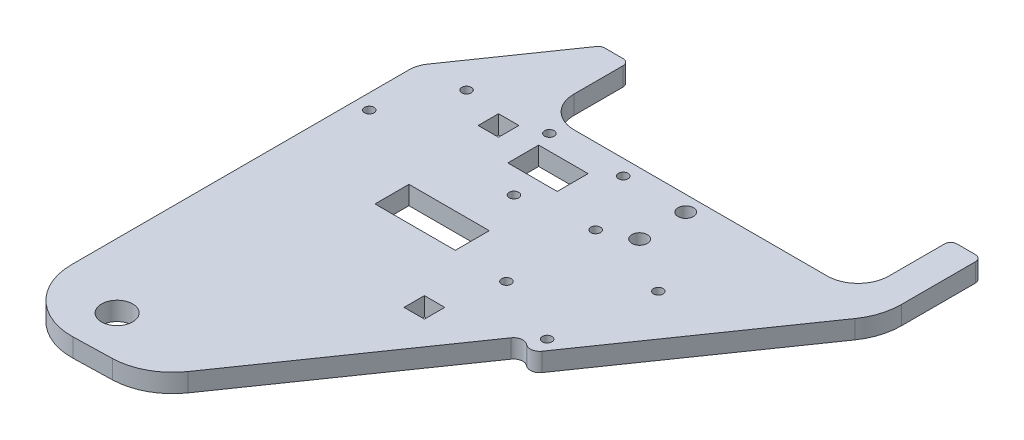
SolidWorks part; units mm, degrees
ref_plane "Płaszczyzna przednia" through (0, 0, 0) normal (0, 0, 1) x (1, 0, 0)
ref_plane "Płaszczyzna górna" through (0, 0, 0) normal (0, 1, 0) x (1, 0, 0)
ref_plane "Płaszczyzna prawa" through (0, 0, 0) normal (1, 0, 0) x (0, 0, -1)
sketch "Szkic2" plane through (0, 0, 0) normal (0, 1, 0) x (1, 0, 0)
  line L0 (-2.7059, 127.916) -> (-8.7059, 127.916)
  line L1 (-14.7059, 84.6961) -> (-30.2059, 84.6961)
  line L2 (-34.2059, 68.0362) -> (-34.2059, 10.6045)
  line L3 (103.2941, 130) -> (109.2941, 130)
  line L4 (56.7941, 30.9358) -> (56.7941, 25.7981)
  line L5 (56.7941, 59.3339) -> (56.7941, 30.9358)
  line L6 (14.1571, -19.1399) -> (-0.0957, -33.3284)
  line L7 (111.2941, 128) -> (111.2941, 110.0131)
  line L9 (9.2941, 100) -> (91.2941, 100)
  line L10 (85.9359, 90.0901) -> (91.3711, 90.0901)
  line L11 (-34.2059, 68.0362) -> (-34.2059, 69.9294)
  line L12 (-10.7059, 125.916) -> (-10.7059, 88.6961)
  line L13 (-34.2059, 69.9294) -> (-34.2059, 80.6961)
  line L14 (-34.2059, 10.6045) -> (-34.2059, -19.1544)
  line L15 (14.1571, -19.1399) -> (55.0272, 21.5459)
  line L26 (-0.7059, 110) -> (-0.7059, 125.916)
  line L28 (101.2941, 128) -> (101.2941, 110)
  arc A0 (56.7941, 25.7981) -> (55.0272, 21.5459) centre (50.7941, 25.7981) cw
  arc A1 (101.2941, 110) -> (91.2941, 100) centre (91.2941, 110) cw
  arc A2 (56.7941, 59.3339) -> (85.9359, 90.0901) centre (85.7027, 61.1269) cw
  arc A3 (-34.2059, -19.1544) -> (-0.0957, -33.3284) centre (-14.2059, -19.1544) ccw
  arc A4 (-34.2059, 80.6961) -> (-30.2059, 84.6961) centre (-30.2059, 80.6961) cw
  arc A5 (111.2941, 110.0131) -> (91.3711, 90.0901) centre (91.3711, 110.0131) cw
  arc A7 (-14.7059, 84.6961) -> (-10.7059, 88.6961) centre (-14.7059, 88.6961) ccw
  arc A8 (-8.7059, 127.916) -> (-10.7059, 125.916) centre (-8.7059, 125.916) ccw
  arc A9 (109.2941, 130) -> (111.2941, 128) centre (109.2941, 128) cw
  arc A10 (-0.7059, 110) -> (9.2941, 100) centre (9.2941, 110) ccw
  arc A11 (101.2941, 128) -> (103.2941, 130) centre (103.2941, 128) cw
  arc A12 (-2.7059, 127.916) -> (-0.7059, 125.916) centre (-2.7059, 125.916) cw
  point P0 (0.6391, -30.8544)
  point P1 (26.0174, 75.6612)
  point P7 (22.4343, 73.3976)
  point P9 (71.2941, 80)
  point P10 (-27.8527, -17.9733)
  point P18 (-27.4825, -20.4307)
  point P21 (71.2941, 110)
  dimension "D8" = 10
  dimension "D11" = 2
  dimension "D12" = 2
  dimension "D14" = 6
  dimension "D7" = 4
  dimension "D4" = 20
  dimension "D2" = 10
  dimension "D3" = 10
  dimension "D6" = 102
extrude "Dodanie-wyciągnięcie1" add sketch "Szkic2" along normal blind 6 separate body
sketch "Szkic3" plane through (0, 6, 0) normal (0, 1, 0) x (1, 0, 0)
  circle A4 centre (-13.2962, -25.3039) radius 5.05
  dimension "D2" = 10.1
  dimension "D1" = 0
extrude "Wytnij-wyciągnięcie1" cut sketch "Szkic3" against normal through all
sketch "Szkic4" plane through (0, 6, 0) normal (0, 1, 0) x (1, 0, 0)
  line L0 (4.8941, 92) -> (4.8941, 98) construction
  line L1 (7.9941, 92) -> (7.9941, 98) construction
  line L2 (31.8941, 92) -> (31.8941, 98) construction
  line L3 (28.7941, 92) -> (28.7941, 98) construction
  line L4 (37.8941, 73.9) -> (43.8941, 73.9) construction
  line L5 (37.8941, 45) -> (43.8941, 45) construction
  line L6 (37.8941, 48.1) -> (43.8941, 48.1) construction
  line L7 (37.8941, 77) -> (43.8941, 77) construction
  line L8 (4.8941, 92) -> (4.8941, 98)
  line L9 (7.9941, 92) -> (7.9941, 98)
  line L10 (31.8941, 92) -> (31.8941, 98)
  line L11 (28.7941, 92) -> (28.7941, 98)
  line L12 (7.827, 95) -> (4.8941, 95)
  line L13 (28.6269, 95) -> (31.8941, 95)
  line L14 (40.8941, 77) -> (40.8941, 73.9)
  line L15 (40.8941, 48.1) -> (40.8941, 45)
  line L36 (37.8941, 73.9) -> (43.8941, 73.9)
  line L37 (37.8941, 45) -> (43.8941, 45)
  line L38 (37.8941, 48.1) -> (43.8941, 48.1)
  line L39 (37.8941, 77) -> (43.8941, 77)
  circle A0 centre (40.8941, 46.55) radius 1.55
  circle A1 centre (40.8941, 75.45) radius 1.55
  circle A2 centre (6.3605, 95) radius 1.55
  circle A3 centre (30.2605, 95) radius 1.55
  dimension "D1" = 3.1
  dimension "D2" = 3.1
  dimension "D3" = 3.1
  dimension "D4" = 3.1
  dimension "D5" = 1.55
  dimension "D6" = 1.55
sketch "Szkic14" plane through (0, 0, 0) normal (0, -1, 0) x (1, 0, 0)
  line L0 (63.4524, -70.496) -> (70.9956, -63.931) construction
  line L1 (65.4876, -72.8344) -> (73.0308, -66.2694) construction
  line L2 (63.4524, -70.496) -> (70.9956, -63.931)
  line L3 (65.4876, -72.8344) -> (73.0308, -66.2694)
  line L4 (67.224, -67.2135) -> (69.2592, -69.5519)
  line L5 (-20.7559, -98.7461) -> (-20.7559, -88.7461) construction
  line L6 (-17.6559, -98.7461) -> (-17.6559, -88.7461) construction
  line L7 (-20.7559, -98.7461) -> (-20.7559, -88.7461)
  line L8 (-17.6559, -98.7461) -> (-17.6559, -88.7461)
  line L9 (-17.6559, -93.7461) -> (-20.7559, -93.7461)
  circle A0 centre (68.2416, -68.3827) radius 1.55
  circle A2 centre (-19.2059, -93.7461) radius 1.55
  dimension "D1" = 3.1
  dimension "D2" = 3.1
sketch "Szkic5" plane through (0, 6, 0) normal (0, 1, 0) x (1, 0, 0)
  line L3 (28.7941, 92) -> (7.9941, 92) construction
  line L4 (37.8941, 48.1) -> (37.8941, 73.9) construction
  line L5 (23.8941, 47) -> (23.8941, 58)
  line L6 (23.8941, 47) -> (-2.1059, 47)
  line L7 (23.8941, 58) -> (-2.1059, 58)
  line L8 (-2.1059, 47) -> (-2.1059, 58)
  line L9 (37.8941, 23) -> (37.8941, 45) construction
  line L10 (-1.1059, 29) -> (31.8941, 29) construction
  line L11 (23.8941, 90) -> (23.8941, 80)
  line L12 (23.8941, 90) -> (7.8941, 90)
  line L13 (23.8941, 80) -> (7.8941, 80)
  line L14 (7.8941, 90) -> (7.8941, 80)
  circle A0 centre (40.8941, 75.45) radius 1.55 construction
  circle A1 centre (30.2605, 95) radius 1.55 construction
  circle A2 centre (6.3605, 95) radius 1.55 construction
  circle A3 centre (40.8941, 46.55) radius 1.55 construction
  circle A4 centre (40.8941, 75.45) radius 1.55
  circle A5 centre (30.2605, 95) radius 1.55
  circle A6 centre (6.3605, 95) radius 1.55
  circle A7 centre (40.8941, 46.55) radius 1.55
  circle A10 centre (17.8941, 72) radius 1.55
  dimension "D1" = 11
  dimension "D2" = 26
  dimension "D4" = 18
  dimension "D5" = 2
  dimension "D6" = 10
  dimension "D9" = 3.1
  dimension "D3" = 14
  dimension "D7" = 20
  dimension "D8" = 20
  dimension "D10" = 16
extrude "Wytnij-wyciągnięcie2" cut sketch "Szkic5" against normal through all
sketch "Szkic12" plane through (0, 0, 0) normal (0, -1, 0) x (1, 0, 0)
  line L0 (28.4064, 21.7668) -> (22.6749, 30.0296)
  line L1 (-1.5055, 38.8356) -> (-13.6937, 39.1478)
  line L2 (55.0272, -21.5459) -> (-13.6937, 39.1478)
  line L4 (111.2941, -110.0131) -> (111.2941, -103.9866)
  line L5 (89.1661, -65.8281) -> (107.7277, -92.5876)
  line L6 (111.2941, -110.0131) -> (91.3711, -90.0901)
  line L7 (-1.5055, 38.8356) -> (6.7535, 38.624)
  line L10 (56.7941, -25.7981) -> (56.7941, -59.3339)
  line L11 (85.9359, -90.0901) -> (91.3711, -90.0901)
  line L12 (62.7753, -27.7816) -> (89.1661, -65.8281)
  line L13 (62.7753, -27.7816) -> (28.4064, 21.7668)
  arc A0 (-0.0957, 33.3284) -> (-34.2059, 19.1544) centre (-14.2059, 19.1544) ccw construction
  arc A1 (6.7535, 38.624) -> (22.6749, 30.0296) centre (6.2413, 18.6306) cw
  arc A2 (111.2941, -103.9866) -> (107.7277, -92.5876) centre (91.2941, -103.9866) ccw
  arc A6 (56.7941, -25.7981) -> (55.0272, -21.5459) centre (50.7941, -25.7981) ccw
  arc A7 (56.7941, -59.3339) -> (85.9359, -90.0901) centre (85.7027, -61.1269) ccw
  dimension "D1" = 20
extrude "Dodanie-wyciągnięcie2" add sketch "Szkic12" against normal blind 6
sketch "Szkic6" plane through (0, 0, 0) normal (0, -1, 0) x (1, 0, 0)
  circle A1 centre (68.2416, -68.3827) radius 1.55 construction
  circle A2 centre (68.2416, -68.3827) radius 1.55
extrude "Wytnij-wyciągnięcie3" cut sketch "Szkic6" against normal through all
sketch "Szkic13" plane through (0, 0, 0) normal (0, -1, 0) x (1, 0, 0)
  line L12 (-34.2059, -80.6961) -> (-34.2059, -90.1835)
  line L13 (11.8543, -159.0896) -> (-73.1985, -36.4725)
  line L14 (-10.3657, -127.0559) -> (-32.7793, -94.7431)
  line L15 (-8.7223, -127.916) -> (-6.2646, -127.916)
  line L16 (-2.7059, -127.916) -> (-8.7059, -127.916) construction
  line L17 (-8.7059, -80.6961) -> (-34.2059, -80.6961)
  line L18 (-6.2646, -127.916) -> (-6.2646, -80.6961)
  line L19 (-6.2646, -80.6961) -> (-8.7059, -80.6961)
  arc A11 (-34.2059, -90.1835) -> (-32.7793, -94.7431) centre (-26.2059, -90.1835) ccw
  arc A12 (-8.7223, -127.916) -> (-10.3657, -127.0559) centre (-8.7223, -125.916) cw
  dimension "D2" = 8
  dimension "D3" = 2
  dimension "D1" = 116.68
extrude "Dodanie-wyciągnięcie3" add sketch "Szkic13" against normal blind 6
sketch "Szkic9" plane through (0, 0, 0) normal (0, -1, 0) x (1, 0, 0)
  line L0 (107.7277, -92.5876) -> (22.6749, 30.0296) construction
  circle A0 centre (63.6687, -36.9649) radius 1.55
  circle A1 centre (-13.2962, 25.3039) radius 5.05 construction
  dimension "D1" = 3.1
  dimension "D2" = 4.5
  dimension "D3" = 99
extrude "Wytnij-wyciągnięcie5" cut sketch "Szkic9" against normal blind 6
sketch "Szkic11" plane through (0, 0, 0) normal (0, -1, 0) x (1, 0, 0)
  circle A0 centre (-29.3372, -72.3879) radius 1.55 construction
  circle A1 centre (-29.3372, -72.3879) radius 1.55
extrude "Wytnij-wyciągnięcie6" cut sketch "Szkic11" against normal blind 6
sketch "Szkic15" plane through (0, 0, 0) normal (0, -1, 0) x (1, 0, 0)
  circle A0 centre (50.5658, -80.0013) radius 2.5 construction
  circle A1 centre (50.4845, -95.0011) radius 2.5 construction
  circle A2 centre (50.5658, -80.0013) radius 2.5
  circle A3 centre (50.4845, -95.0011) radius 2.5
extrude "Wytnij-wyciągnięcie7" cut sketch "Szkic15" against normal blind 6
sketch "Szkic8" plane through (0, 0, 0) normal (0, -1, 0) x (1, 0, 0)
  circle A2 centre (-19.2059, -93.7461) radius 1.55 construction
  circle A3 centre (-19.2059, -93.7461) radius 1.55
extrude "Wytnij-wyciągnięcie4" cut sketch "Szkic8" against normal through all
sketch "Szkic17" plane through (0, 0, 0) normal (0, -1, 0) x (1, 0, 0)
  line L0 (31.8941, -29) -> (31.8941, -23) construction
  line L1 (31.8941, -29) -> (31.8941, -23)
  line L2 (31.8941, -23) -> (37.8941, -23) construction
  line L3 (37.8941, -23) -> (37.8941, -29) construction
  line L4 (37.8941, -29) -> (31.8941, -29) construction
  line L5 (31.8941, -23) -> (37.8941, -23)
  line L6 (37.8941, -23) -> (37.8941, -29)
  line L7 (37.8941, -29) -> (31.8941, -29)
  line L8 (-1.1059, -86) -> (-1.1059, -92) construction
  line L9 (-1.1059, -92) -> (-7.1059, -92) construction
  line L10 (38.1941, -29.3) -> (31.5941, -29.3)
  line L11 (31.5941, -29.3) -> (31.5941, -22.7)
  line L12 (31.5941, -22.7) -> (38.1941, -22.7)
  line L13 (38.1941, -22.7) -> (38.1941, -29.3)
  line L14 (-0.8059, -85.7) -> (-0.8059, -92.3)
  line L15 (-0.8059, -92.3) -> (-7.4059, -92.3)
  line L16 (-7.4059, -92.3) -> (-7.4059, -85.7)
  line L17 (-7.4059, -85.7) -> (-0.8059, -85.7)
  line L30 (-7.1059, -86) -> (-1.1059, -86) construction
  line L31 (-7.1059, -92) -> (-7.1059, -86) construction
  line L32 (-1.1059, -86) -> (-1.1059, -92)
  line L33 (-1.1059, -92) -> (-7.1059, -92)
  line L34 (-7.1059, -86) -> (-1.1059, -86)
  line L35 (-7.1059, -92) -> (-7.1059, -86)
  dimension "D1" = 0.3
  dimension "D2" = 0.3
sketch "Szkic20" plane through (0, 0, 0) normal (0, -1, 0) x (1, 0, 0)
  line L0 (38.1941, -22.7) -> (38.1941, -29.3) construction
  line L1 (38.1941, -29.3) -> (31.5941, -29.3) construction
  line L2 (31.5941, -29.3) -> (31.5941, -22.7) construction
  line L3 (31.5941, -22.7) -> (38.1941, -22.7) construction
  line L4 (-0.8059, -85.7) -> (-0.8059, -92.3) construction
  line L5 (-0.8059, -92.3) -> (-7.4059, -92.3) construction
  line L6 (-7.4059, -92.3) -> (-7.4059, -85.7) construction
  line L7 (-7.4059, -85.7) -> (-0.8059, -85.7) construction
  line L8 (38.1941, -22.7) -> (38.1941, -29.3)
  line L9 (38.1941, -29.3) -> (31.5941, -29.3)
  line L10 (31.5941, -29.3) -> (31.5941, -22.7)
  line L11 (31.5941, -22.7) -> (38.1941, -22.7)
  line L12 (-0.8059, -85.7) -> (-0.8059, -92.3)
  line L13 (-0.8059, -92.3) -> (-7.4059, -92.3)
  line L14 (-7.4059, -92.3) -> (-7.4059, -85.7)
  line L15 (-7.4059, -85.7) -> (-0.8059, -85.7)
extrude "Wytnij-wyciągnięcie9" cut sketch "Szkic20" against normal blind 6
sketch "Szkic21" plane through (0, 0, 0) normal (0, -1, 0) x (1, 0, 0)
  line L0 (62.0515, -32.0016) -> (61.6406, -32.2866)
  line L1 (66.2263, -32.7568) -> (22.6749, 30.0296)
  line L2 (57.4657, -31.5314) -> (14.6211, 30.2359)
  line L3 (6.7535, 38.624) -> (-1.3002, 38.8303)
  line L4 (107.7277, -92.5876) -> (22.6749, 30.0296) construction
  line L5 (6.7535, 38.624) -> (-13.6937, 39.1478) construction
  circle A0 centre (63.6687, -36.9649) radius 1.55 construction
  arc A1 (61.6406, -32.2866) -> (57.4657, -31.5314) centre (59.9308, -29.8215) cw
  arc A2 (66.2263, -32.7568) -> (62.0515, -32.0016) centre (63.7613, -34.4666) ccw
  arc A3 (-1.3002, 38.8303) -> (14.6211, 30.2359) centre (-1.8124, 18.8369) cw
  arc A4 (22.6749, 30.0296) -> (6.7535, 38.624) centre (6.2413, 18.6306) ccw construction
  arc A5 (22.6749, 30.0296) -> (6.7535, 38.624) centre (6.2413, 18.6306) ccw
  point P13 (64.5165, -30.2917)
  dimension "D2" = 5
  dimension "D1" = 3
  dimension "D3" = 20
extrude "Wytnij-wyciągnięcie10" cut sketch "Szkic21" against normal blind 10
equation "\"tolerancja_wpusy\"=0.2"
equation "\"dlugosc_wpustu_duzy\"=20"
equation "\"srednica_otworu_M3\"=3.1"
equation "\"szerokosc_nogi_T\"=3.1"
equation "\"dlugosc_T_30\"=11"
equation "\"grubosc_na_nakretke_kwadrat\"=2"
equation "\"szerokosc_na_nakretke_kwadrat\"=5.85"
equation "\"wyokosc_nadstawki_T\"=0.5"
equation "\"dlugosc_T_20_6\"=14"
equation "\"D1@Szkic4\"=\"srednica_otworu_M3\""
equation "\"D2@Szkic4\"=\"srednica_otworu_M3\""
equation "\"D3@Szkic4\"=\"srednica_otworu_M3\""
equation "\"D4@Szkic4\"=\"srednica_otworu_M3\""
equation "\"D9@Szkic5\"=\"srednica_otworu_M3\""
equation "\"D5@Szkic4\"=\"srednica_otworu_M3\"/2"
equation "\"D6@Szkic4\"=\"srednica_otworu_M3\"/2"
equation "\"D1@Szkic9\"=\"srednica_otworu_M3\""
equation "\"D1@Szkic14\"=\"srednica_otworu_M3\""
